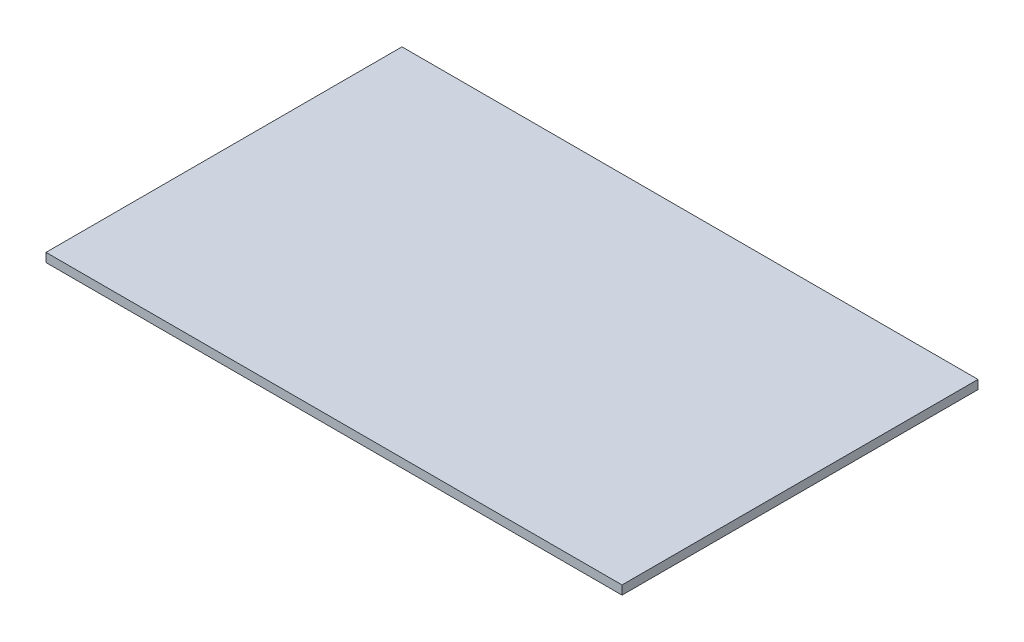
SolidWorks part; units mm, degrees
material "Perspex (TM) GS Acrylic Cast Sheet"
ref_plane "Front Plane" through (0, 0, 0) normal (0, 0, 1) x (1, 0, 0)
ref_plane "Top Plane" through (0, 0, 0) normal (0, 1, 0) x (1, 0, 0)
ref_plane "Right Plane" through (0, 0, 0) normal (1, 0, 0) x (0, 0, -1)
sketch "Sketch1" plane through (0, 0, 0) normal (0, 1, 0) x (1, 0, 0)
  line L1 (0, 0) -> (412, 0)
  line L2 (0, 0) -> (0, 254.6)
  line L3 (0, 254.6) -> (412, 254.6)
  line L4 (412, 0) -> (412, 254.6)
  dimension "D1" = 254.6
  dimension "D2" = 412
extrude "Boss-Extrude1" add sketch "Sketch1" along normal blind 6.35
equation "\"D1@Sketch1\"=280-25.4"
